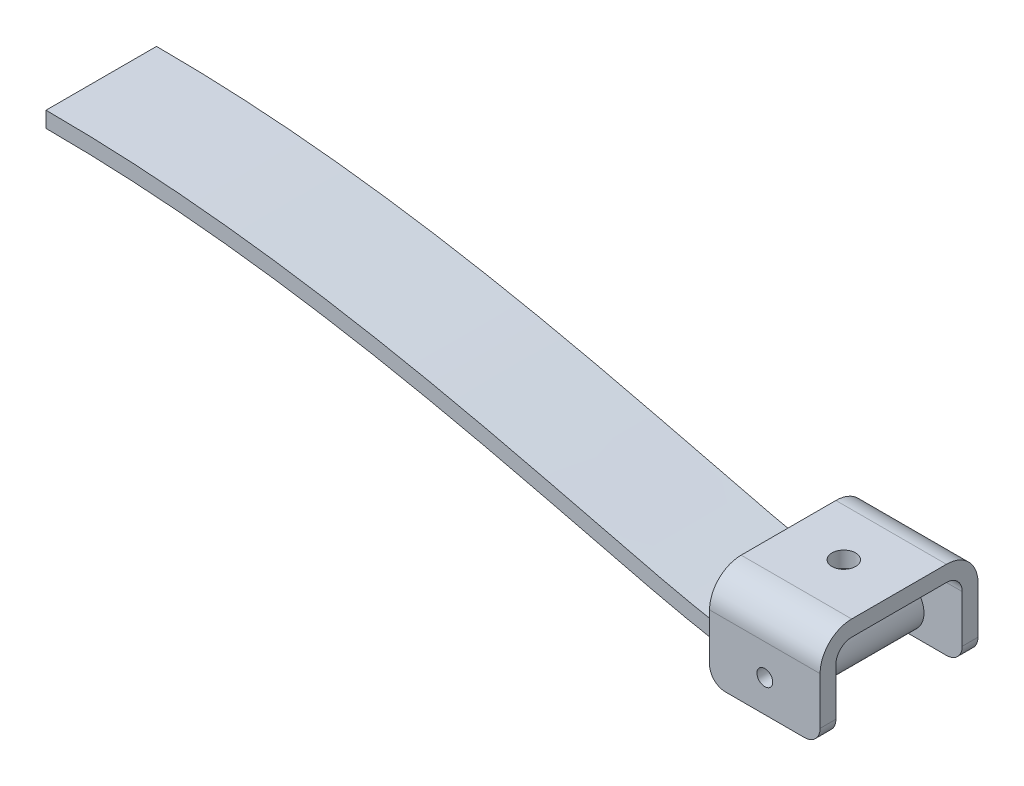
SolidWorks part; units mm, degrees
ref_plane "Front Plane" through (0, 0, 0) normal (0, 0, 1) x (1, 0, 0)
ref_plane "Top Plane" through (0, 0, 0) normal (0, 1, 0) x (1, 0, 0)
ref_plane "Right Plane" through (0, 0, 0) normal (1, 0, 0) x (0, 0, -1)
sketch "Sketch1" plane through (0, 0, 0) normal (0, 0, 1) x (1, 0, 0)
  line L0 (115.824, 0) -> (-119.8608, 0) construction
  line L1 (-215.2856, 46.228) -> (-377.702, 46.228) construction
  line L2 (-289.56, 39.878) -> (-289.56, 46.228)
  line L3 (0, 0) -> (19.05, 0)
  line L4 (19.05, 0) -> (19.05, -6.35)
  line L5 (19.05, -6.35) -> (0, -6.35)
  line L6 (9.525, 0) -> (9.525, 3.175) construction
  circle A0 centre (9.525, 3.175) radius 9.525
  circle A1 centre (9.525, 3.175) radius 3.175
  spline S0 degree 3 poles (-289.56, 46.228) (-153.1954, 46.228) (-42.1279, 0) (0, 0) knots 0 0 0 0 1 1 1 1
  spline S1 degree 1 poles (-289.56, 39.878) (0, -6.35) knots 0 0 1 1 construction
  spline S2 degree 3 poles (-289.56, 39.878) (-287.4577, 39.878) (-283.2444, 39.8557) (-274.8883, 39.7244) (-264.5301, 39.4032) (-252.2622, 38.783) (-236.1261, 37.6651) (-216.3928, 35.7637) (-193.4747, 32.809) (-171.3823, 29.3145) (-143.111, 24.1135) (-110.1519, 16.9303) (-80.7791, 9.7286) (-59.666, 4.4891) (-45.0759, 0.9533) (-31.7764, -2.0559) (-21.7966, -4.0132) (-14.4788, -5.1792) (-9.3178, -5.8347) (-5.2906, -6.1809) (-2.2109, -6.325) (-0.7431, -6.35) (0, -6.35) knots 0 0 0 0 0.015625 0.03125 0.0625 0.09375 0.125 0.1875 0.25 0.3125 0.375 0.5 0.625 0.6875 0.75 0.8125 0.875 0.90625 0.9375 0.96875 0.984375 1 1 1 1
  dimension "D5" = 19.05
  dimension "D6" = 6.35
  dimension "D1" = 289.56
  dimension "D2" = 46.228
  dimension "D4" = 19.05
  dimension "D3" = 6.35
extrude "Boss-Extrude1" add sketch "Sketch1" along normal mid plane 44.45 contours L2 S2 L5 A0 L3 S0 | L3 A0 | L3 A0
sketch "Sketch2" plane through (0, 0, 0) normal (1, 0, 0) x (0, 0, -1)
  line L0 (-32.244, -9.743) -> (-32.244, 15.657)
  line L1 (-19.544, 28.357) -> (18.556, 28.357)
  line L2 (31.256, 15.657) -> (31.256, -9.743)
  line L3 (0, 0) -> (0, 28.357) construction
  arc A0 (18.556, 28.357) -> (31.256, 15.657) centre (18.556, 15.657) cw
  arc A1 (-32.244, 15.657) -> (-19.544, 28.357) centre (-19.544, 15.657) cw
  dimension "D1" = 12.7
  dimension "D2" = 38.1
  dimension "D3" = 63.5
extrude "Extrude-Thin1" add sketch "Sketch2" along normal blind 44.45 from offset 12.7 separate body thin offset against normal yes
sketch "Sketch3" plane through (0, 0, 32.244) normal (0, 0, 1) x (1, 0, 0)
  circle A0 centre (9.525, 3.175) radius 3.175
  circle A1 centre (9.525, 3.175) radius 3.175 construction
extrude "Cut-Extrude1" cut sketch "Sketch3" against normal through all
fillet "Fillet1" radius 6.35 4 edges at (31.75, -9.743, -28.081) (-12.7, -9.743, -28.081) (31.75, -9.743, 29.069) (-12.7, -9.743, 29.069)
sketch "Sketch4" plane through (0, 28.357, 0) normal (0, 1, 0) x (1, 0, 0)
  line L0 (9.525, -19.544) -> (9.525, 18.556) construction
  line L1 (31.75, -19.544) -> (-12.7, -19.544) construction
  line L2 (31.75, 18.556) -> (-12.7, 18.556) construction
  circle A0 centre (9.525, -0.494) radius 4.7625
  dimension "D1" = 9.525
extrude "Cut-Extrude2" cut sketch "Sketch4" against normal blind 6.35
